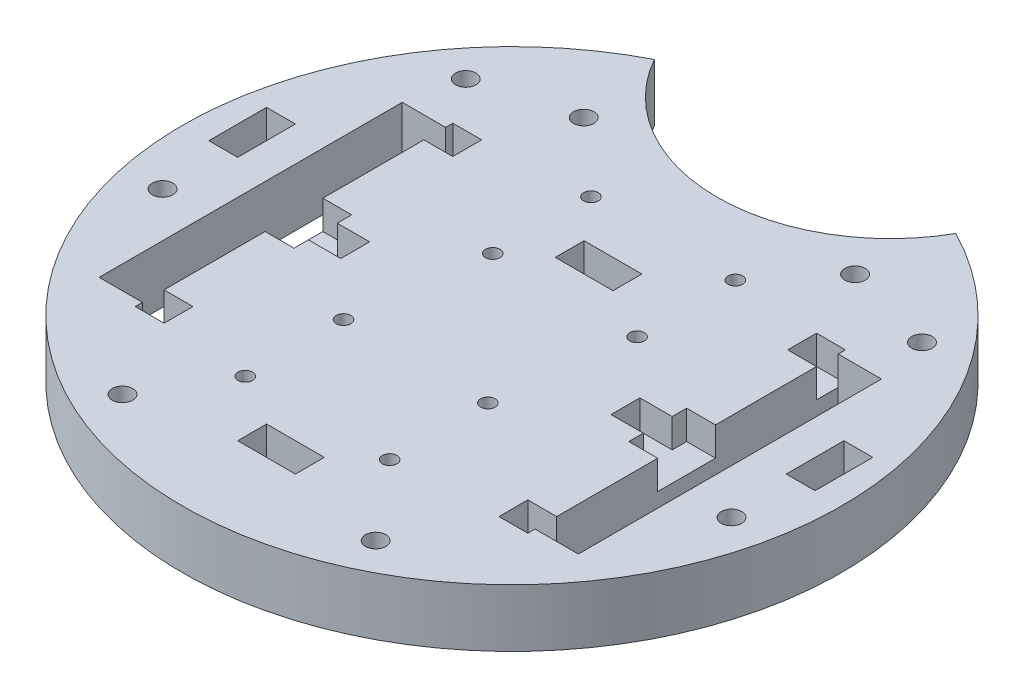
SolidWorks part; units mm, degrees
ref_plane "Front Plane" through (0, 0, 0) normal (0, 0, 1) x (1, 0, 0)
ref_plane "Top Plane" through (0, 0, 0) normal (0, 1, 0) x (1, 0, 0)
ref_plane "Right Plane" through (0, 0, 0) normal (1, 0, 0) x (0, 0, -1)
sketch "Sketch1" plane through (0, 0, 0) normal (0, 1, 0) x (1, 0, 0)
  line L0 (-33.1606, 64.4719) -> (0, 83.2333) construction
  line L1 (0, 83.2333) -> (33.1606, 64.4719) construction
  line L2 (-33.1606, 64.4719) -> (33.1606, 64.4719) construction
  circle A0 centre (0, 0) radius 72.5
  circle A1 centre (0, 83.2333) radius 38.1
  dimension "D1" = 145
  dimension "D2" = 76.2
  dimension "D3" = 121
extrude "Boss-Extrude1" add sketch "Sketch1" along normal blind 12.7 contours A1 A0
sketch "Sketch2" plane through (0, 12.7, 0) normal (0, 1, 0) x (1, 0, 0)
  line L0 (0, 0) -> (0, -21.4465) construction
  line L1 (43.18, -38.1) -> (43.18, 28.575)
  line L2 (-43.18, -38.1) -> (-52.705, -38.1)
  line L3 (-43.18, -38.1) -> (-43.18, 28.575)
  line L4 (-43.18, 28.575) -> (-52.705, 28.575)
  line L5 (-52.705, -38.1) -> (-52.705, 28.575)
  line L6 (-47.9425, 28.575) -> (-47.9425, -38.1) construction
  line L7 (-43.18, -4.7625) -> (-52.705, -4.7625) construction
  line L8 (43.18, -38.1) -> (52.705, -38.1)
  line L9 (52.705, -38.1) -> (52.705, 28.575)
  line L10 (43.18, 28.575) -> (52.705, 28.575)
  point P3 (-47.9425, -4.7625)
  dimension "D1" = 43.18
  dimension "D2" = 9.525
  dimension "D3" = 66.675
  dimension "D4" = 28.575
extrude "Cut-Extrude1" cut sketch "Sketch2" against normal through all
sketch "Sketch3" plane through (0, 12.7, 0) normal (0, 1, 0) x (1, 0, 0)
  line L0 (13.97, -19.2716) -> (13.97, -40.8716) construction
  line L1 (0, 8.0693) -> (0, 0) construction
  line L2 (0, 0) -> (8.2737, 0) construction
  line L3 (-43.18, -38.1) -> (-43.18, 28.575) construction
  line L4 (-13.97, 31.3466) -> (17.78, 31.3466) construction
  line L5 (-13.97, 9.7466) -> (-13.97, 31.3466) construction
  line L6 (13.97, -40.8716) -> (-17.78, -40.8716) construction
  line L7 (-43.18, -40.8716) -> (-17.78, -40.8716) construction
  line L8 (17.78, 31.3466) -> (43.18, 31.3466) construction
  line L9 (-43.18, -4.7625) -> (-33.5195, -4.7625) construction
  line L10 (13.97, -30.0716) -> (1.6655, -30.0716) construction
  line L11 (-13.97, 20.5466) -> (-28.5261, 20.5466) construction
  line L12 (43.18, 28.575) -> (43.18, -38.1) construction
  circle A0 centre (-17.78, -40.8716) radius 1.6
  circle A1 centre (13.97, -40.8716) radius 1.6
  circle A2 centre (13.97, -19.2716) radius 1.6
  circle A3 centre (-17.78, -19.2716) radius 1.6
  circle A4 centre (-13.97, 9.7466) radius 1.6
  circle A5 centre (17.78, 9.7466) radius 1.6
  circle A6 centre (17.78, 31.3466) radius 1.6
  circle A7 centre (-13.97, 31.3466) radius 1.6
  point P22 (-17.78, -40.8716)
  dimension "D4" = 3.2
  dimension "D1" = 31.75
  dimension "D2" = 21.6
  dimension "D3" = 25.4
  dimension "D5" = 25.3091
  dimension "D6" = 25.3091
extrude "Cut-Extrude2" cut sketch "Sketch3" against normal through all and the other way through all
hole_wizard "CBORE for #4 Binding Head Machine Screw1" [suppressed] positions "Sketch5" profile "Sketch7" counterbore size "#4" standard "ANSI Inch"
sketch "Sketch5" plane through (0, 0, 0) normal (0, -1, 0) x (-1, 0, 0)
  line L4 (0, 16.1887) -> (0, -6.35) construction
  line L5 (0, -6.35) -> (-10.0248, -6.35) construction
  point P0 (-31.75, 38.1)
  point P3 (31.75, 38.1)
  point P6 (31.75, -50.8)
  point P9 (-31.75, -50.8)
  dimension "D1" = 6.35
  dimension "D2" = 88.9
  dimension "D3" = 63.5
sketch "Sketch7" plane through (31.75, 0, -38.1) normal (1, 0, 0) x (0, 0, -1)
  line L0 (0, 0) -> (0, 12.7)
  line L1 (0, 12.7) -> (1.6319, 12.7)
  line L3 (1.6319, 12.7) -> (1.6319, 6.35)
  line L4 (1.6319, 6.35) -> (3.3731, 6.35)
  line L5 (3.3731, 6.35) -> (3.3731, 0)
  line L7 (3.3731, 0) -> (0, 0)
  line L11 (0, -6.35) -> (0, 107.95) construction
  dimension "Thru Hole Dia." = 3.2639
  dimension "Thru Hole Depth" = 12.7
  dimension "C'Bore Dia." = 6.7462
  dimension "C'Bore Depth" = 6.35
sketch "Sketch8" plane through (0, 12.7, 0) normal (0, 1, 0) x (1, 0, 0)
  line L0 (-43.18, -38.1) -> (-43.18, 28.575) construction
  line L1 (-36.83, -11.1125) -> (-43.18, -11.1125)
  line L2 (-36.83, -11.1125) -> (-36.83, -7.9375)
  line L3 (-36.83, 1.5875) -> (-43.18, 1.5875)
  line L4 (-43.18, -11.1125) -> (-43.18, 1.5875)
  line L5 (-40.005, 1.5875) -> (-40.005, -11.1125) construction
  line L6 (-34.9112, -4.7625) -> (-43.18, -4.7625) construction
  line L7 (-43.18, -39.6875) -> (-43.18, -33.3375)
  line L8 (-36.83, 30.1625) -> (-43.18, 30.1625)
  line L9 (-36.83, 30.1625) -> (-36.83, 23.8125)
  line L10 (-36.83, 23.8125) -> (-43.18, 23.8125)
  line L11 (-43.18, 30.1625) -> (-43.18, 23.8125)
  line L12 (-36.83, -33.3375) -> (-43.18, -33.3375)
  line L13 (-36.83, -39.6875) -> (-36.83, -33.3375)
  line L14 (-36.83, -39.6875) -> (-43.18, -39.6875)
  line L15 (-36.83, -1.5875) -> (-36.83, 1.5875)
  line L16 (-29.718, -1.5875) -> (-36.83, -1.5875)
  line L17 (-29.718, -1.5875) -> (-29.718, -7.9375)
  line L18 (-29.718, -7.9375) -> (-36.83, -7.9375)
  line L20 (-33.274, -7.9375) -> (-33.274, -1.5875) construction
  line L21 (-29.718, -4.7625) -> (-34.9112, -4.7625) construction
  point P0 (-40.005, -4.7625)
  point P14 (-33.274, -4.7625)
  dimension "D1" = 6.35
  dimension "D2" = 12.7
  dimension "D3" = 57.15
  dimension "D4" = 6.35
  dimension "D5" = 7.112
  dimension "D6" = 6.35
extrude "Cut-Extrude3" cut sketch "Sketch8" against normal blind 6.35
mirror "Mirror1" about plane through (0, 0, 0) normal (1, 0, 0) of "Cut-Extrude3"
sketch "Sketch9" plane through (0, 0, 0) normal (0, -1, 0) x (1, 0, 0)
  line L0 (3.1087, -68.0797) -> (4.9303, -63.4384) [skipped]
  line L1 (55.1651, -40.0165) -> (52.6721, -35.6985)
  line L2 (52.6721, -35.6985) -> (47.6861, -35.6985)
  line L3 (47.6861, -35.6985) -> (45.1931, -40.0165)
  line L4 (45.1931, -40.0165) -> (47.6861, -44.3345)
  line L5 (47.6861, -44.3345) -> (52.6721, -44.3345)
  line L6 (52.6721, -44.3345) -> (55.1651, -40.0165)
  line L7 (4.9303, -63.4384) -> (1.8216, -59.5402) [skipped]
  line L8 (1.8216, -59.5402) -> (-3.1087, -60.2833) [skipped]
  line L9 (-3.1087, -60.2833) -> (-4.9303, -64.9246) [skipped]
  line L10 (-4.9303, -64.9246) -> (-1.8216, -68.8228) [skipped]
  line L11 (-1.8216, -68.8228) -> (3.1087, -68.0797) [skipped]
  line L12 (-51.2886, -44.8775) -> (-46.5241, -43.4078)
  line L13 (-46.5241, -43.4078) -> (-45.4146, -38.5469)
  line L14 (-45.4146, -38.5469) -> (-49.0696, -35.1555)
  line L15 (-49.0696, -35.1555) -> (-53.8341, -36.6252)
  line L16 (-53.8341, -36.6252) -> (-54.9436, -41.4862)
  line L17 (-54.9436, -41.4862) -> (-51.2886, -44.8775)
  line L18 (-67.0646, 12.1184) -> (-62.9449, 9.3097)
  line L19 (-62.9449, 9.3097) -> (-58.4527, 11.473)
  line L20 (-58.4527, 11.473) -> (-58.0801, 16.4451)
  line L21 (-58.0801, 16.4451) -> (-62.1997, 19.2538)
  line L22 (-62.1997, 19.2538) -> (-66.692, 17.0904)
  line L23 (-66.692, 17.0904) -> (-67.0646, 12.1184)
  line L24 (-32.3395, 59.9889) -> (-31.9669, 55.0168)
  line L25 (-31.9669, 55.0168) -> (-27.4747, 52.8535)
  line L26 (-27.4747, 52.8535) -> (-23.3551, 55.6622)
  line L27 (-23.3551, 55.6622) -> (-23.7277, 60.6342)
  line L28 (-23.7277, 60.6342) -> (-28.2199, 62.7976)
  line L29 (-28.2199, 62.7976) -> (-32.3395, 59.9889)
  line L30 (26.7378, 62.6865) -> (23.0828, 59.2952)
  line L31 (23.0828, 59.2952) -> (24.1923, 54.4342)
  line L32 (24.1923, 54.4342) -> (28.9568, 52.9645)
  line L33 (28.9568, 52.9645) -> (32.6118, 56.3559)
  line L34 (32.6118, 56.3559) -> (31.5023, 61.2169)
  line L35 (31.5023, 61.2169) -> (26.7378, 62.6865)
  line L36 (65.6811, 18.1799) -> (60.7507, 18.9231)
  line L37 (60.7507, 18.9231) -> (57.642, 15.0249)
  line L38 (57.642, 15.0249) -> (59.4636, 10.3835)
  line L39 (59.4636, 10.3835) -> (64.3939, 9.6404)
  line L40 (64.3939, 9.6404) -> (67.5026, 13.5386)
  line L41 (67.5026, 13.5386) -> (65.6811, 18.1799)
  line L43 (34.831, -45.632) -> (32.338, -41.314)
  line L44 (32.338, -41.314) -> (27.352, -41.314)
  line L45 (27.352, -41.314) -> (24.859, -45.632)
  line L46 (24.859, -45.632) -> (27.352, -49.95)
  line L47 (27.352, -49.95) -> (32.338, -49.95)
  line L48 (32.338, -49.95) -> (34.831, -45.632)
  line L49 (-24.859, -45.632) -> (-27.352, -41.314)
  line L50 (-27.352, -41.314) -> (-32.338, -41.314)
  line L51 (-32.338, -41.314) -> (-34.831, -45.632)
  line L52 (-34.831, -45.632) -> (-32.338, -49.95)
  line L53 (-32.338, -49.95) -> (-27.352, -49.95)
  line L54 (-27.352, -49.95) -> (-24.859, -45.632)
  circle A0 centre (-50.1791, -40.0165) radius 2.1527
  circle A1 centre (-62.5723, 14.2817) radius 2.1527
  circle A2 centre (-27.8473, 57.8255) radius 2.1527
  circle A3 centre (27.8473, 57.8255) radius 2.1527
  circle A4 centre (62.5723, 14.2817) radius 2.1527
  circle A5 centre (50.1791, -40.0165) radius 2.1527
  circle A6 centre (50.1791, -40.0165) radius 4.318 construction
  circle A7 centre (0, -64.1815) radius 2.1527 [skipped]
  circle A8 centre (0, -64.1815) radius 4.318 construction
  circle A9 centre (-50.1791, -40.0165) radius 2.1527
  circle A10 centre (-50.1791, -40.0165) radius 4.318 construction
  circle A11 centre (-62.5723, 14.2817) radius 2.1527
  circle A12 centre (-62.5723, 14.2817) radius 4.318 construction
  circle A13 centre (-27.8473, 57.8255) radius 2.1527
  circle A14 centre (-27.8473, 57.8255) radius 4.318 construction
  circle A15 centre (27.8473, 57.8255) radius 2.1527
  circle A16 centre (27.8473, 57.8255) radius 4.318 construction
  circle A17 centre (62.5723, 14.2817) radius 2.1527
  circle A18 centre (62.5723, 14.2817) radius 4.318 construction
  circle A19 centre (29.845, -45.632) radius 2.1527
  circle A20 centre (-29.845, -45.632) radius 2.1527
  circle A21 centre (29.845, -45.632) radius 4.318 construction
  circle A22 centre (-29.845, -45.632) radius 4.318 construction
  point P12 (0, 0)
  point P77 (0, 0)
  dimension "D1" = 8.636
  dimension "D2" = 7
extrude "Cut-Extrude4" cut sketch "Sketch9" against normal blind 6.35 contours L5 L6 L1 L2 L3 L4 A5 | L40 L41 L36 L37 L38 L39 A4 | L34 L35 L30 L31 L32 L33 A3 | L28 L29 L24 L25 L26 L27 A2 | L16 L17 L12 L13 L14 L15 A0 | L22 L23 L18 L19 L20 L21 A1 | L53 L54 L49 L50 L51 L52 A20 | L47 L48 L43 L44 L45 L46 A19
hole_wizard "#8 Clearance Hole1" positions "Sketch10" profile "Sketch11" hole size "#8" standard "ANSI Inch" end condition through all
sketch "Sketch10" plane through (0, 0, 0) normal (0, -1, 0) x (-1, 0, 0)
  point P0 (-50.1791, 40.0165)
  point P3 (-62.5723, -14.2817)
  point P6 (-27.8473, -57.8255)
  point P9 (27.8473, -57.8255)
  point P12 (62.5723, -14.2817)
  point P15 (50.1791, 40.0165)
  point P22 (-29.845, 45.632)
  point P25 (29.845, 45.632)
sketch "Sketch11" plane through (50.1791, 0, -40.0165) normal (1, 0, 0) x (0, 0, -1)
  line L0 (0, 0) -> (0, 12.7)
  line L1 (0, 12.7) -> (2.2479, 12.7)
  line L2 (2.2479, 12.7) -> (2.2479, 0)
  line L5 (2.2479, 0) -> (0, 0)
  line L11 (0, -6.35) -> (0, 107.95) construction
  dimension "Thru Hole Dia." = 4.4958
  dimension "Thru Hole Depth" = 12.7
sketch "Sketch12" plane through (0, 12.7, 0) normal (0, 1, 0) x (1, 0, 0)
  line L0 (-29.718, -7.9375) -> (-29.718, -1.5875) construction
  line L1 (-27.178, 3.81) -> (-20.828, 3.81)
  line L2 (-27.178, 3.81) -> (-27.178, -2.54)
  line L3 (-27.178, -2.54) -> (-20.828, -2.54)
  line L4 (-20.828, 3.81) -> (-20.828, -2.54)
  line L5 (20.828, 3.81) -> (27.178, 3.81)
  line L6 (20.828, 3.81) -> (20.828, -2.54)
  line L7 (20.828, -2.54) -> (27.178, -2.54)
  line L8 (27.178, 3.81) -> (27.178, -2.54)
  line L9 (0, 0) -> (0, 14.5543) construction
  dimension "D1" = 6.35
  dimension "D2" = 2.54
  dimension "D3" = 3.81
extrude "Cut-Extrude5" [suppressed] cut sketch "Sketch12" against normal blind 6.35
sketch "Sketch13" plane through (0, 0, 0) normal (0, -1, 0) x (1, 0, 0)
  circle A0 centre (0, 63.5) radius 2.921
  circle A1 centre (0, -38.1) radius 2.921
  dimension "D1" = 5.842
  dimension "D2" = 63.5
  dimension "D3" = 38.1
extrude "Cut-Extrude6" cut sketch "Sketch13" against normal blind 6.35
sketch "Sketch14" plane through (0, 0, 0) normal (0, -1, 0) x (1, 0, 0)
  line L1 (21.3729, -31.3466) -> (19.5764, -28.2351)
  line L2 (19.5764, -28.2351) -> (15.9836, -28.2351)
  line L3 (15.9836, -28.2351) -> (14.1871, -31.3466)
  line L4 (14.1871, -31.3466) -> (15.9836, -34.4581)
  line L5 (15.9836, -34.4581) -> (19.5764, -34.4581)
  line L6 (19.5764, -34.4581) -> (21.3729, -31.3466)
  line L7 (-10.3771, -9.7466) -> (-12.1736, -6.6351)
  line L8 (-10.3771, -31.3466) -> (-12.1736, -28.2351)
  line L9 (-12.1736, -28.2351) -> (-15.7664, -28.2351)
  line L10 (-15.7664, -28.2351) -> (-17.5629, -31.3466)
  line L11 (-17.5629, -31.3466) -> (-15.7664, -34.4581)
  line L12 (-15.7664, -34.4581) -> (-12.1736, -34.4581)
  line L13 (-12.1736, -34.4581) -> (-10.3771, -31.3466)
  line L14 (-12.1736, -6.6351) -> (-15.7664, -6.6351)
  line L15 (-15.7664, -6.6351) -> (-17.5629, -9.7466)
  line L16 (-17.5629, -9.7466) -> (-15.7664, -12.8581)
  line L17 (-15.7664, -12.8581) -> (-12.1736, -12.8581)
  line L18 (-12.1736, -12.8581) -> (-10.3771, -9.7466)
  line L19 (14.1871, -9.7466) -> (15.9836, -12.8581)
  line L20 (15.9836, -12.8581) -> (19.5764, -12.8581)
  line L21 (19.5764, -12.8581) -> (21.3729, -9.7466)
  line L22 (21.3729, -9.7466) -> (19.5764, -6.6351)
  line L23 (19.5764, -6.6351) -> (15.9836, -6.6351)
  line L24 (15.9836, -6.6351) -> (14.1871, -9.7466)
  line L25 (17.5629, 19.2716) -> (15.7664, 22.3831)
  line L26 (15.7664, 22.3831) -> (12.1736, 22.3831)
  line L27 (12.1736, 22.3831) -> (10.3771, 19.2716)
  line L28 (10.3771, 19.2716) -> (12.1736, 16.1601)
  line L29 (12.1736, 16.1601) -> (15.7664, 16.1601)
  line L30 (15.7664, 16.1601) -> (17.5629, 19.2716)
  line L31 (-14.1871, 19.2716) -> (-15.9836, 22.3831)
  line L32 (-15.9836, 22.3831) -> (-19.5764, 22.3831)
  line L33 (-19.5764, 22.3831) -> (-21.3729, 19.2716)
  line L34 (-21.3729, 19.2716) -> (-19.5764, 16.1601)
  line L35 (-19.5764, 16.1601) -> (-15.9836, 16.1601)
  line L36 (-15.9836, 16.1601) -> (-14.1871, 19.2716)
  line L37 (-14.1871, 40.8716) -> (-15.9836, 43.9831)
  line L38 (-15.9836, 43.9831) -> (-19.5764, 43.9831)
  line L39 (-19.5764, 43.9831) -> (-21.3729, 40.8716)
  line L40 (-21.3729, 40.8716) -> (-19.5764, 37.7601)
  line L41 (-19.5764, 37.7601) -> (-15.9836, 37.7601)
  line L42 (-15.9836, 37.7601) -> (-14.1871, 40.8716)
  line L43 (10.3771, 40.8716) -> (12.1736, 37.7601)
  line L44 (12.1736, 37.7601) -> (15.7664, 37.7601)
  line L45 (15.7664, 37.7601) -> (17.5629, 40.8716)
  line L46 (17.5629, 40.8716) -> (15.7664, 43.9831)
  line L47 (15.7664, 43.9831) -> (12.1736, 43.9831)
  line L48 (12.1736, 43.9831) -> (10.3771, 40.8716)
  circle A0 centre (17.78, -31.3466) radius 3.1115 construction
  circle A1 centre (-13.97, -31.3466) radius 3.1115 construction
  circle A2 centre (-13.97, -9.7466) radius 3.1115 construction
  circle A3 centre (17.78, -9.7466) radius 3.1115 construction
  circle A4 centre (13.97, 19.2716) radius 3.1115 construction
  circle A5 centre (-17.78, 19.2716) radius 3.1115 construction
  circle A6 centre (-17.78, 40.8716) radius 3.1115 construction
  circle A7 centre (13.97, 40.8716) radius 3.1115 construction
  dimension "D1" = 6.223
extrude "Cut-Extrude7" cut sketch "Sketch14" against normal blind 6.35
sketch "Sketch15" plane through (0, 12.7, 0) normal (0, 1, 0) x (1, 0, 0)
  line L0 (0, 0) -> (0, -15.7206) construction
  line L1 (6.35, 15.875) -> (-6.35, 15.875)
  line L2 (6.35, 15.875) -> (6.35, 22.225)
  line L3 (6.35, 22.225) -> (-6.35, 22.225)
  line L4 (-6.35, 15.875) -> (-6.35, 22.225)
  line L5 (0, 22.225) -> (0, 15.875) construction
  line L6 (6.35, 19.05) -> (-6.35, 19.05) construction
  line L7 (6.35, -53.975) -> (-6.35, -53.975)
  line L8 (6.35, -53.975) -> (6.35, -47.625)
  line L9 (6.35, -47.625) -> (-6.35, -47.625)
  line L10 (-6.35, -53.975) -> (-6.35, -47.625)
  line L11 (0, -47.625) -> (0, -53.975) construction
  line L12 (6.35, -50.8) -> (-6.35, -50.8) construction
  line L13 (-60.325, 12.7) -> (-66.675, 12.7)
  line L14 (-60.325, 12.7) -> (-60.325, 0)
  line L15 (-60.325, 0) -> (-66.675, 0)
  line L16 (-66.675, 12.7) -> (-66.675, 0)
  line L17 (-63.5, 0) -> (-63.5, 12.7) construction
  line L18 (-60.325, 6.35) -> (-66.675, 6.35) construction
  line L19 (60.325, 12.7) -> (60.325, 0)
  line L20 (60.325, 0) -> (66.675, 0)
  line L21 (66.675, 12.7) -> (66.675, 0)
  line L22 (60.325, 12.7) -> (66.675, 12.7)
  point P0 (0, 19.05)
  point P4 (0, -50.8)
  point P8 (-63.5, 6.35)
  dimension "D1" = 6.35
  dimension "D2" = 12.7
  dimension "D3" = 19.05
  dimension "D4" = 50.8
  dimension "D5" = 63.5
  dimension "D6" = 6.35
extrude "Cut-Extrude8" cut sketch "Sketch15" against normal through all
equation "\"D6@Sketch3\"=\"D5@Sketch3\""
